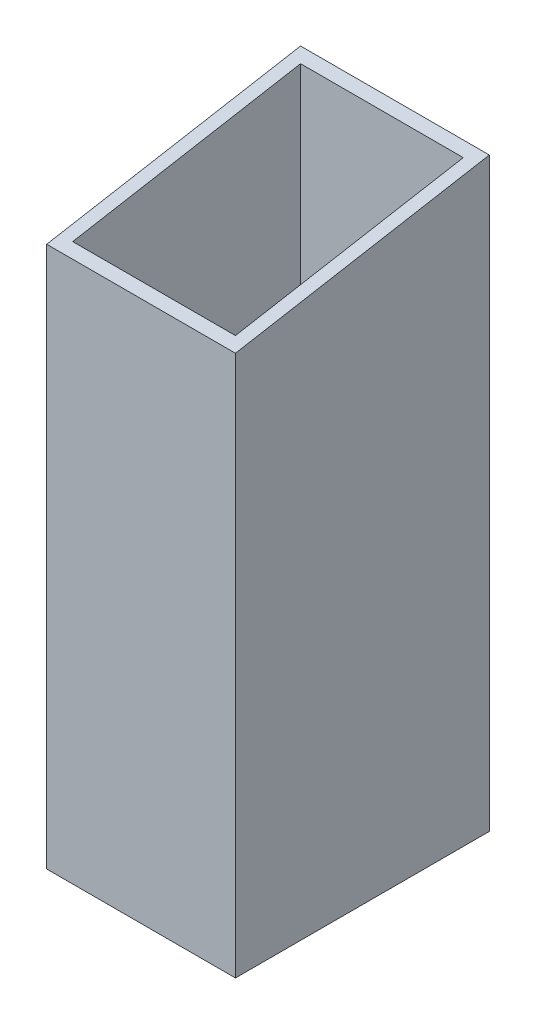
SolidWorks part; units mm, degrees
ref_plane "Front Plane" through (0, 0, 0) normal (0, 0, 1) x (1, 0, 0)
ref_plane "Top Plane" through (0, 0, 0) normal (0, 1, 0) x (1, 0, 0)
ref_plane "Right Plane" through (0, 0, 0) normal (1, 0, 0) x (0, 0, -1)
sketch "Sketch1" plane through (0, 0, 0) normal (0, 1, 0) x (1, 0, 0)
  line L1 (0, 0) -> (29, 0)
  line L2 (0, 0) -> (0, 39)
  line L3 (0, 39) -> (29, 39)
  line L4 (29, 0) -> (29, 39)
  dimension "D1" = 39
  dimension "D2" = 29
extrude "Boss-Extrude1" add sketch "Sketch1" along normal blind 90
shell "Shell1" thickness 2
sketch "Sketch3" plane through (0, 0, 0) normal (-1, 0, 0) x (0, 0, 1)
  line L0 (-39, 90) -> (0, 83.1232)
  line L1 (0, 90) -> (0, 0) construction
extrude "Cut-Extrude1" cut sketch "Sketch3" against normal through all and the other way through all
